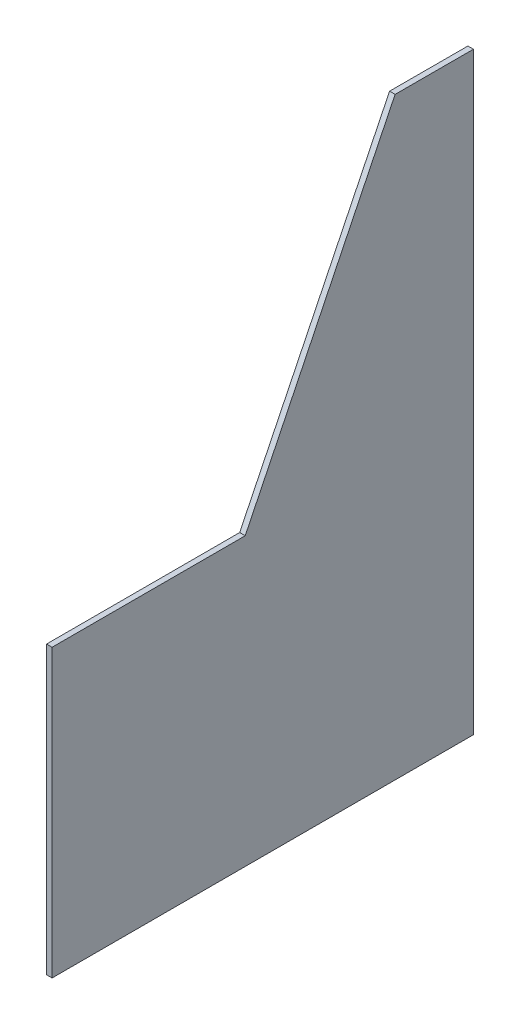
SolidWorks part; units mm, degrees
ref_plane "Front" through (0, 0, 0) normal (0, 0, 1) x (1, 0, 0)
ref_plane "Top" through (0, 0, 0) normal (0, 1, 0) x (1, 0, 0)
ref_plane "Right" through (0, 0, 0) normal (1, 0, 0) x (0, 0, -1)
sketch "Эскиз1" plane through (0, 0, 0) normal (1, 0, 0) x (0, 0, -1)
  line L0 (456, 642.5) -> (371.1973, 642.5538)
  line L1 (371.1973, 642.5538) -> (209, 310)
  line L2 (209, 310) -> (0, 310)
  line L3 (0, 310) -> (0, 0)
  line L4 (0, 0) -> (456, 0)
  line L5 (456, 0) -> (456, 642.5)
extrude "Бобышка-Вытянуть1" add sketch "Эскиз1" along normal blind 6
